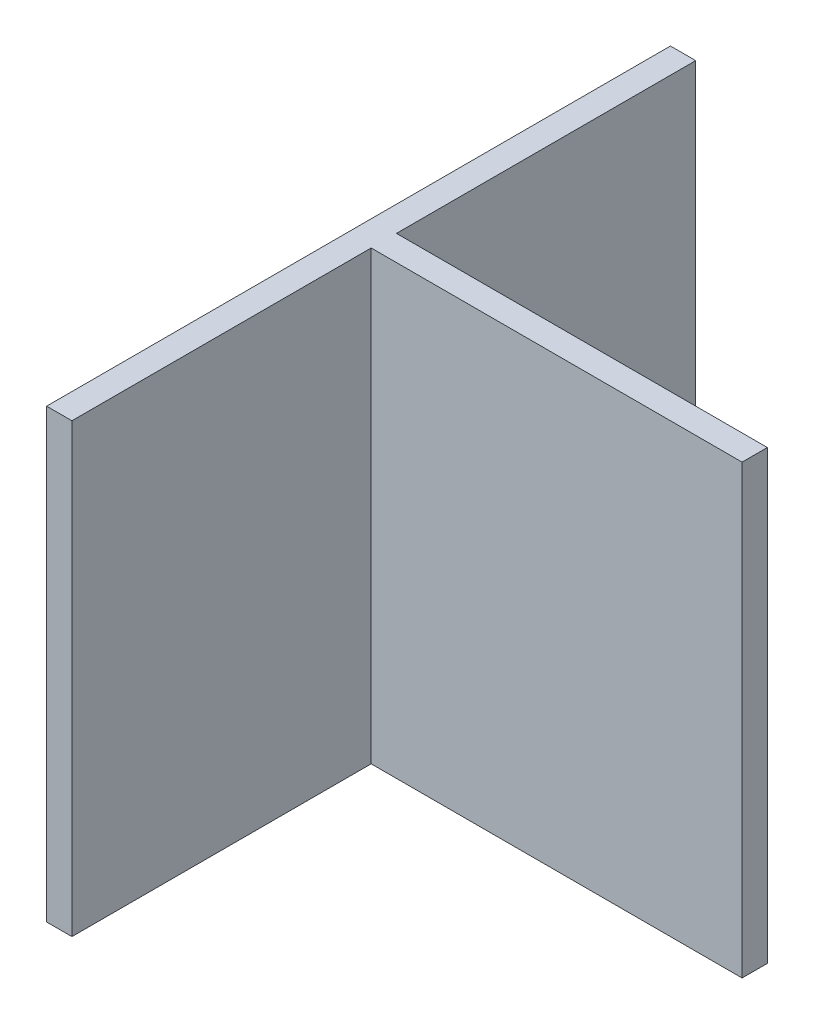
SolidWorks part; units mm, degrees
ref_plane "Front Plane" through (0, 0, 0) normal (0, 0, 1) x (1, 0, 0)
ref_plane "Top Plane" through (0, 0, 0) normal (0, 1, 0) x (1, 0, 0)
ref_plane "Right Plane" through (0, 0, 0) normal (1, 0, 0) x (0, 0, -1)
sketch "Sketch1" plane through (0, 0, 0) normal (0, 1, 0) x (1, 0, 0)
  line L0 (0, 0) -> (1193.8, 0) construction
  line L1 (-76.2, -1879.6) -> (76.2, -1879.6)
  line L2 (-76.2, -1879.6) -> (-76.2, 1879.6)
  line L3 (-76.2, 1879.6) -> (76.2, 1879.6)
  line L4 (76.2, -1879.6) -> (76.2, 1879.6)
  line L5 (-76.2, -1879.6) -> (76.2, 1879.6) construction
  line L6 (-76.2, 1879.6) -> (76.2, -1879.6) construction
  line L8 (2311.4, 76.2) -> (76.2, 76.2)
  line L9 (2311.4, 76.2) -> (2311.4, -76.2)
  line L10 (2311.4, -76.2) -> (76.2, -76.2)
  line L11 (76.2, 76.2) -> (76.2, -76.2)
  line L12 (2311.4, 76.2) -> (76.2, -76.2) construction
  line L13 (2311.4, -76.2) -> (76.2, 76.2) construction
  point P0 (0, 0)
  dimension "D1" = 3759.2
  dimension "D2" = 152.4
  dimension "D3" = 152.4
  dimension "D4" = 2235.2
extrude "Boss-Extrude1" add sketch "Sketch1" along normal blind 2692.4 contours L1 L4 L3 L2 | L10 L9 L8 L4
